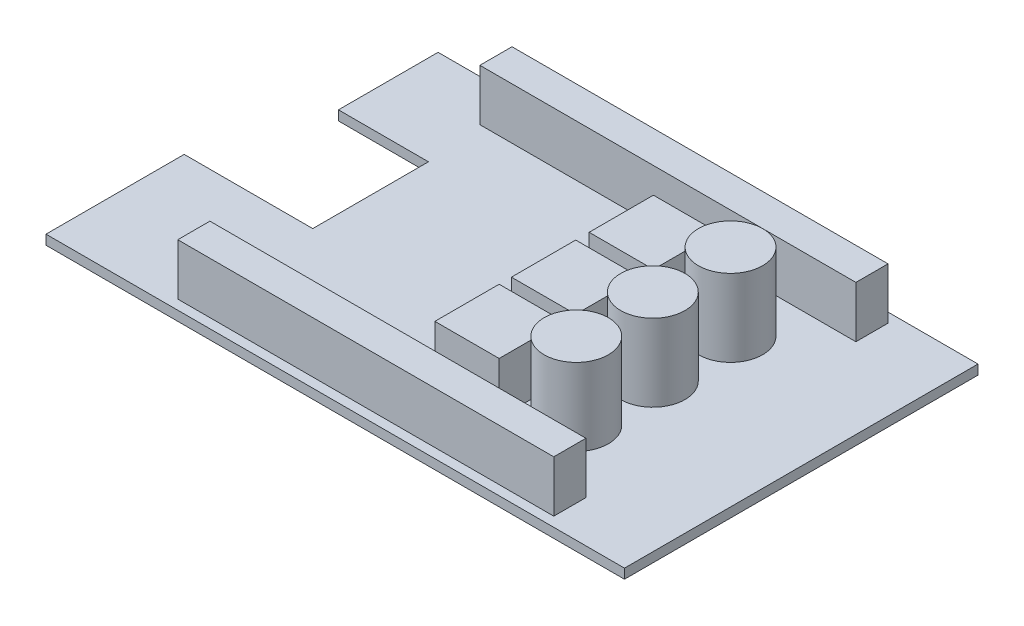
SolidWorks part; units mm, degrees
ref_plane "Front Plane" through (0, 0, 0) normal (0, 0, 1) x (1, 0, 0)
ref_plane "Top Plane" through (0, 0, 0) normal (0, 1, 0) x (1, 0, 0)
ref_plane "Right Plane" through (0, 0, 0) normal (1, 0, 0) x (0, 0, -1)
sketch "Sketch1" plane through (0, 0, 0) normal (0, 1, 0) x (1, 0, 0)
  line L0 (0, 0) -> (0, -21.5)
  line L1 (0, -21.5) -> (90, -21.5)
  line L2 (90, -21.5) -> (90, 33.5)
  line L3 (90, 33.5) -> (6, 33.5)
  line L4 (6, 33.5) -> (6, 18)
  line L5 (6, 18) -> (20, 18)
  line L6 (20, 18) -> (20, 0)
  line L7 (20, 0) -> (0, 0)
  dimension "D1" = 90
  dimension "D2" = 55
  dimension "D3" = 84
  dimension "D4" = 21.5
  dimension "D5" = 20
  dimension "D6" = 18
extrude "Boss-Extrude1" add sketch "Sketch1" along normal blind 1.5
sketch "Sketch2" plane through (0, 1.5, 0) normal (0, 1, 0) x (1, 0, 0)
  line L0 (0, 0) -> (0, -21.5) construction
  line L1 (19, -20) -> (77.5, -20)
  line L2 (19, -20) -> (19, -15)
  line L3 (19, -15) -> (77.5, -15)
  line L4 (77.5, -20) -> (77.5, -15)
  line L5 (0, -21.5) -> (90, -21.5) construction
  line L6 (90, 33.5) -> (6, 33.5) construction
  line L7 (19, 32) -> (77.5, 32)
  line L8 (19, 32) -> (19, 27)
  line L9 (19, 27) -> (77.5, 27)
  line L10 (77.5, 32) -> (77.5, 27)
  line L11 (90, -21.5) -> (90, 33.5) construction
  dimension "D1" = 19
  dimension "D2" = 58.5
  dimension "D3" = 1.5
  dimension "D4" = 5
  dimension "D5" = 1.5
  dimension "D6" = 58.5
  dimension "D7" = 12.5
  dimension "D8" = 12.5
  dimension "D9" = 5
extrude "Boss-Extrude2" add sketch "Sketch2" along normal blind 8
sketch "Sketch3" plane through (0, 1.5, 0) normal (0, 1, 0) x (1, 0, 0)
  line L0 (19, 27) -> (77.5, 27) construction
  line L1 (19, 27) -> (77.5, 27) construction
  line L2 (77.5, -15) -> (19, -15) construction
  line L3 (55, 27) -> (55, 23) construction
  line L4 (50, 13) -> (60, 13)
  line L5 (50, 13) -> (50, 23)
  line L6 (50, 23) -> (60, 23)
  line L7 (60, 13) -> (60, 23)
  line L8 (50, 13) -> (60, 23) construction
  line L9 (50, 23) -> (60, 13) construction
  line L10 (50, 0.9124) -> (60, 0.9124)
  line L11 (50, 0.9124) -> (50, 10.9124)
  line L12 (50, 10.9124) -> (60, 10.9124)
  line L13 (60, 0.9124) -> (60, 10.9124)
  line L14 (50, 0.9124) -> (60, 10.9124) construction
  line L15 (50, 10.9124) -> (60, 0.9124) construction
  line L16 (50, -11) -> (60, -11)
  line L17 (50, -11) -> (50, -1)
  line L18 (50, -1) -> (60, -1)
  line L19 (60, -11) -> (60, -1)
  line L20 (50, -11) -> (60, -1) construction
  line L21 (50, -1) -> (60, -11) construction
  line L22 (55, 13) -> (55, 10.9124) construction
  line L23 (55, -1) -> (55, 0.9124) construction
  line L24 (55, -15) -> (55, -11) construction
  line L28 (77.5, 27) -> (77.5, 32) construction
  point P6 (55, 18)
  point P11 (55, 5.9124)
  point P16 (55, -6)
  dimension "D1" = 10
  dimension "D2" = 10
  dimension "D3" = 4
  dimension "D4" = 4
  dimension "D5" = 2.0876
  dimension "D6" = 17.5
extrude "Boss-Extrude3" add sketch "Sketch3" along normal up to surface (8 mm away) up to face at (48.25, 9.5, -29.5)
sketch "Sketch4" plane through (0, 1.5, 0) normal (0, 1, 0) x (1, 0, 0)
  line L0 (60, 18) -> (67, 18) construction
  line L1 (60, 13) -> (60, 23) construction
  line L2 (60, 5.9124) -> (67, 5.9124) construction
  line L3 (60, 0.9124) -> (60, 10.9124) construction
  line L4 (60, -6) -> (67, -6) construction
  line L5 (60, -11) -> (60, -1) construction
  circle A0 centre (67, 18) radius 5
  circle A1 centre (67, 5.9124) radius 5
  circle A2 centre (67, -6) radius 5
  dimension "D1" = 10
  dimension "D2" = 7
extrude "Boss-Extrude4" add sketch "Sketch4" along normal offset from surface (12 mm away) 4 up to face at (55, 9.5, -18) offset beyond the face yes
equation "\"D5@Sketch2\"=\"D3@Sketch2\""
equation "\"D6@Sketch2\"=\"D2@Sketch2\""
equation "\"D8@Sketch2\"=\"D7@Sketch2\""
equation "\"D9@Sketch2\"=\"D4@Sketch2\""
